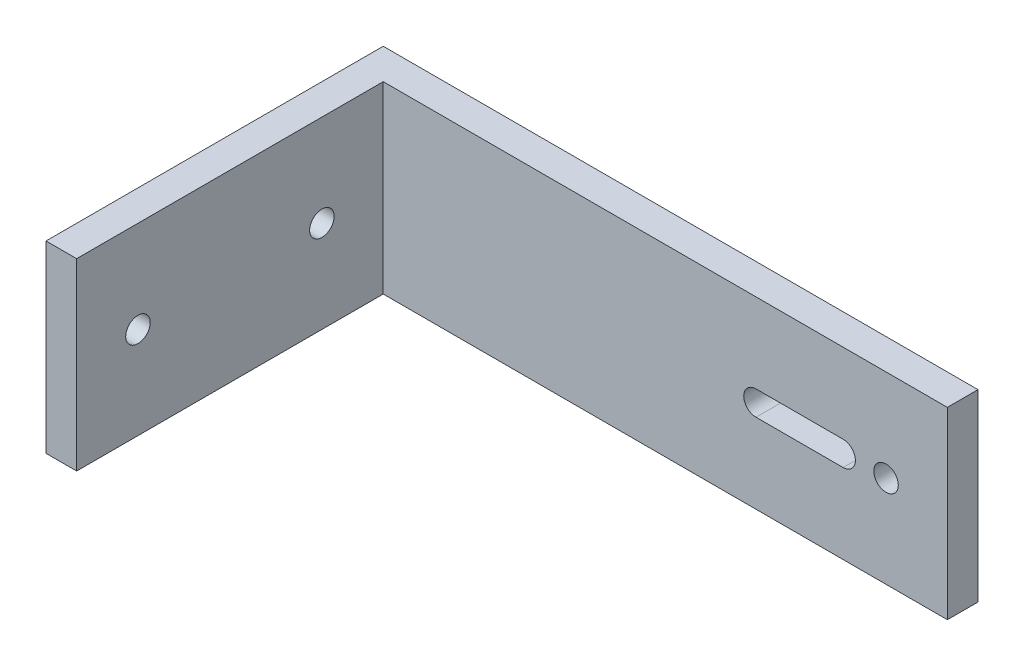
SolidWorks part; units mm, degrees
ref_plane "Front Plane" through (0, 0, 0) normal (0, 0, 1) x (1, 0, 0)
ref_plane "Top Plane" through (0, 0, 0) normal (0, 1, 0) x (1, 0, 0)
ref_plane "Right Plane" through (0, 0, 0) normal (1, 0, 0) x (0, 0, -1)
sketch "Sketch1" plane through (0, 0, 0) normal (0, 0, 1) x (1, 0, 0)
  line L1 (-48.5, 15) -> (48.5, 15)
  line L2 (-48.5, 15) -> (-48.5, -15)
  line L3 (-48.5, -15) -> (48.5, -15)
  line L4 (48.5, 15) -> (48.5, -15)
  line L5 (-48.5, 15) -> (48.5, -15) construction
  line L6 (-48.5, -15) -> (48.5, 15) construction
  point P0 (0, 0)
  dimension "D1" = 30
  dimension "D2" = 97
extrude "Boss-Extrude1" add sketch "Sketch1" along normal blind 5
sketch "Sketch2" plane through (0, 0, 5) normal (0, 0, 1) x (1, 0, 0)
  line L0 (48.5, 15) -> (-48.5, 15) construction
  line L1 (17.2922, 0) -> (31.5, 0) construction
  line L2 (17.2922, 2) -> (31.5, 2)
  line L3 (17.2922, -2) -> (31.5, -2)
  line L4 (48.5, -15) -> (48.5, 15) construction
  circle A0 centre (38.5, 0) radius 2
  arc A1 (17.2922, 2) -> (17.2922, -2) centre (17.2922, 0) ccw
  arc A2 (31.5, -2) -> (31.5, 2) centre (31.5, 0) ccw
  point P2 (24.3961, 0)
  dimension "D1" = 4
  dimension "D2" = 15
  dimension "D3" = 2
  dimension "D5" = 10
  dimension "D4" = 7
extrude "Cut-Extrude1" cut sketch "Sketch2" against normal through all
sketch "Sketch3" plane through (0, 0, 5) normal (0, 0, 1) x (1, 0, 0)
  line L0 (-48.5, -15) -> (48.5, -15) construction
  line L1 (-48.5, 15) -> (-43.5, 15)
  line L2 (-48.5, 15) -> (-48.5, -15)
  line L3 (-48.5, -15) -> (-43.5, -15)
  line L4 (-43.5, 15) -> (-43.5, -15)
  dimension "D1" = 5
extrude "Boss-Extrude2" add sketch "Sketch3" along normal blind 50
sketch "Sketch4" plane through (-48.5, 0, 0) normal (-1, 0, 0) x (0, 0, 1)
  line L0 (0, 15) -> (0, -15) construction
  circle A0 centre (15, 0) radius 2
  circle A1 centre (45, 0) radius 2
  dimension "D1" = 4
  dimension "D2" = 4
  dimension "D4" = 30
  dimension "D3" = 15
extrude "Cut-Extrude2" cut sketch "Sketch4" against normal through all
